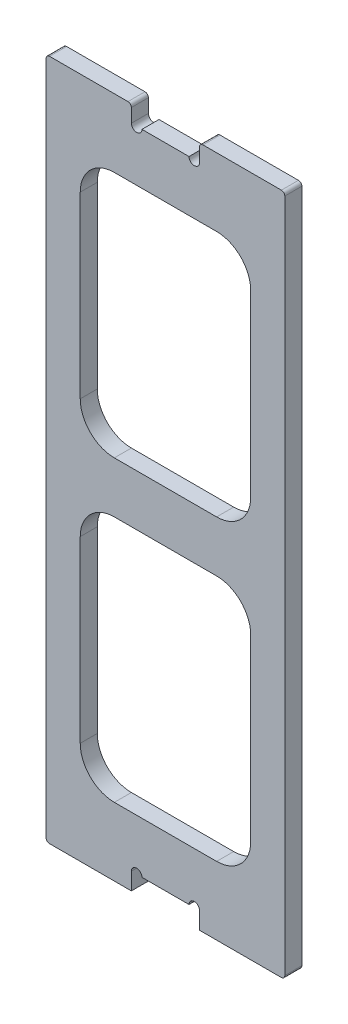
SolidWorks part; units mm, degrees
material "Hexcel AS4C (3000 丝)"
ref_plane "前视基准面" through (0, 0, 0) normal (0, 0, 1) x (1, 0, 0)
ref_plane "上视基准面" through (0, 0, 0) normal (0, 1, 0) x (1, 0, 0)
ref_plane "右视基准面" through (0, 0, 0) normal (1, 0, 0) x (0, 0, -1)
other "Configuration Table"
sketch "草图1" plane through (0, 0, 0) normal (0, 0, 1) x (1, 0, 0)
  line L1 (0, 0) -> (70, 0)
  line L2 (0, 0) -> (0, 190)
  line L3 (0, 190) -> (70, 190)
  line L4 (70, 0) -> (70, 190)
  line L5 (45, 0) -> (70, 0)
  line L6 (45, 0) -> (45, -5)
  line L7 (45, -5) -> (70, -5)
  line L8 (70, 0) -> (70, -5)
  line L9 (0, 0) -> (25, 0)
  line L10 (0, 0) -> (0, -5)
  line L11 (0, -5) -> (25, -5)
  line L12 (25, 0) -> (25, -5)
  line L13 (70, 190) -> (45, 190)
  line L14 (70, 190) -> (70, 195)
  line L15 (70, 195) -> (45, 195)
  line L16 (45, 190) -> (45, 195)
  line L17 (0, 190) -> (25, 190)
  line L18 (0, 190) -> (0, 195)
  line L19 (0, 195) -> (25, 195)
  line L20 (25, 190) -> (25, 195)
  dimension "D1" = 70
  dimension "D2" = 190
  dimension "D3" = 25
  dimension "D4" = 25
  dimension "D5" = 5
  dimension "D6" = 5
  dimension "D7" = 25
  dimension "D8" = 25
  dimension "D9" = 5
  dimension "D10" = 5
extrude "凸台-拉伸1" add sketch "草图1" along normal blind 5 contours L16 L3 L14 L15 | L1 L4 L3 L2 | L3 L20 L19 L18 | L8 L1 L6 L7 | L12 L1 L10 L11
sketch "草图2" plane through (0, 0, 5) normal (0, 0, 1) x (1, 0, 0)
  line L0 (25, 0) -> (45, 0) construction
  line L1 (45, 0) -> (45, -5) construction
  line L2 (25, 0) -> (25, -5) construction
  line L3 (25, 190) -> (45, 190) construction
  line L4 (25, 190) -> (25, 195) construction
  line L5 (45, 190) -> (45, 195) construction
  circle A0 centre (43.45, 0) radius 1.55
  circle A1 centre (26.55, 0) radius 1.55
  circle A2 centre (43.45, 190) radius 1.55
  circle A3 centre (26.55, 190) radius 1.55
  dimension "D4" = 3.1
extrude "切除-拉伸1" cut sketch "草图2" against normal blind 5
sketch "草图3" plane through (0, 0, 5) normal (0, 0, 1) x (1, 0, 0)
  line L0 (-53.1567, 95) -> (111.5166, 95) construction
  line L1 (35, -9.6754) -> (35, 200.1889) construction
  line L2 (70, -5) -> (70, 195) construction
  line L3 (0, -5) -> (0, 195) construction
  line L4 (45, -5) -> (70, -5) construction
  line L5 (70, 195) -> (45, 195) construction
  line L6 (28.1, 0) -> (41.9, 0) construction
  line L7 (10, 87.5) -> (60, 87.5)
  line L8 (10, 87.5) -> (10, 15)
  line L9 (10, 15) -> (60, 15)
  line L10 (60, 87.5) -> (60, 15)
  line L11 (10, 175) -> (60, 175)
  line L12 (10, 102.5) -> (60, 102.5)
  line L13 (10, 102.5) -> (10, 175)
  line L14 (60, 102.5) -> (60, 175)
  dimension "D1" = 7.5
  dimension "D2" = 10
  dimension "D3" = 10
  dimension "D4" = 15
extrude "切除-拉伸2" cut sketch "草图3" against normal up to surface (5 mm away) up to face at (35, 95, 0)
fillet "圆角1" radius 10 8 edges at (10, 15, 2.5) (60, 15, 2.5) (60, 87.5, 2.5) (10, 87.5, 2.5) (10, 102.5, 2.5) (60, 102.5, 2.5) (10, 175, 2.5) (60, 175, 2.5)
fillet "圆角2" radius 1 6 edges at (25, 195, 2.5) (45, 195, 2.5) (0, 195, 2.5) (70, 195, 2.5) (0, -5, 2.5) (70, -5, 2.5)
